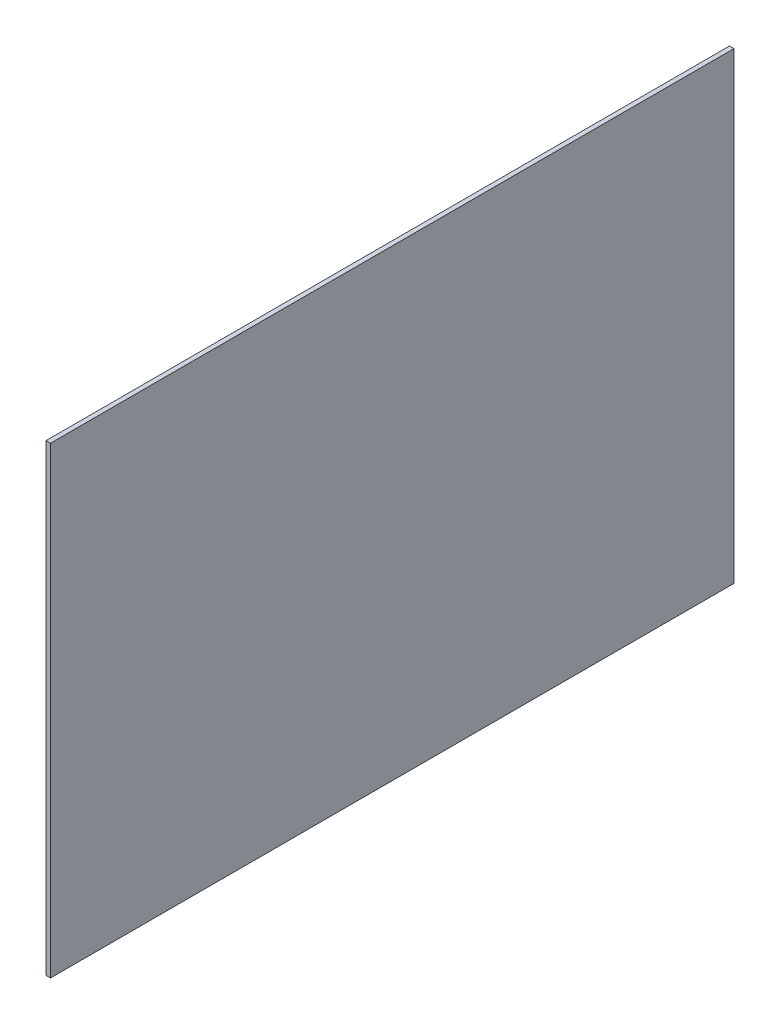
SolidWorks part; units mm, degrees
ref_plane "Front Plane" through (0, 0, 0) normal (0, 0, 1) x (1, 0, 0)
ref_plane "Top Plane" through (0, 0, 0) normal (0, 1, 0) x (1, 0, 0)
ref_plane "Right Plane" through (0, 0, 0) normal (1, 0, 0) x (0, 0, -1)
sketch "Sketch1" plane through (0, 0, 0) normal (1, 0, 0) x (0, 0, -1)
  line L1 (-228.6, 154.9) -> (228.6, 154.9)
  line L2 (-228.6, 154.9) -> (-228.6, -154.9)
  line L3 (-228.6, -154.9) -> (228.6, -154.9)
  line L4 (228.6, 154.9) -> (228.6, -154.9)
  line L5 (-228.6, 154.9) -> (228.6, -154.9) construction
  line L6 (-228.6, -154.9) -> (228.6, 154.9) construction
  point P0 (0, 0)
  dimension "D1" = 457.2
  dimension "D2" = 309.8
extrude "Boss-Extrude1" add sketch "Sketch1" along normal blind 3
